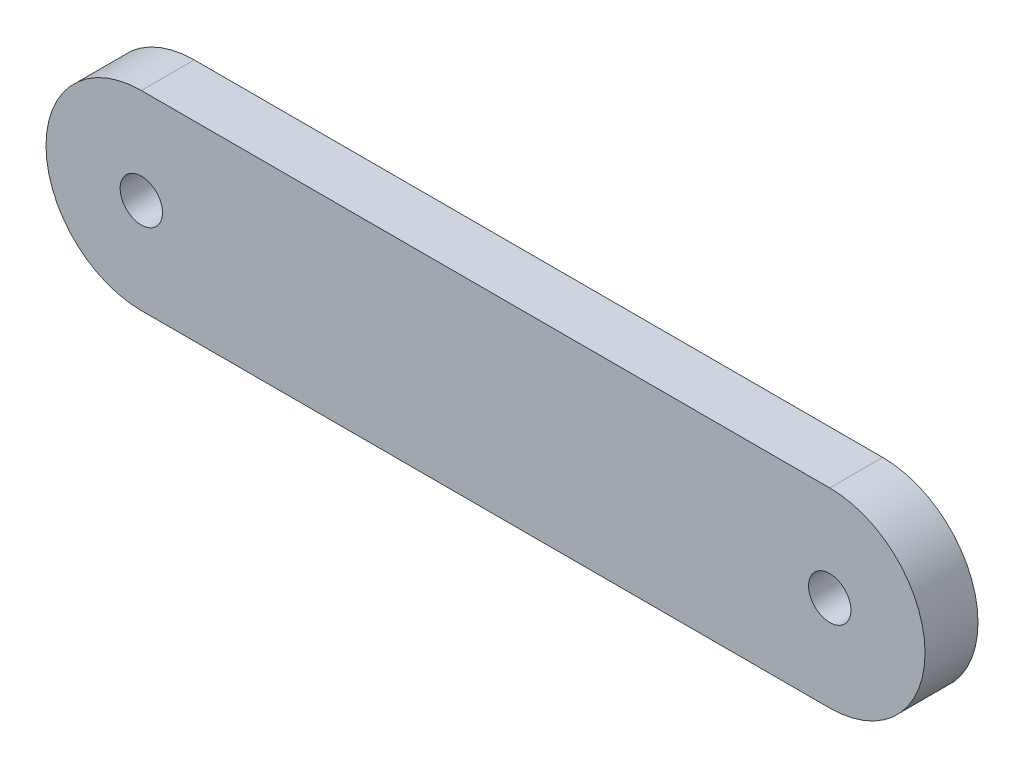
SolidWorks part; units mm, degrees
ref_plane "Plan de face" through (0, 0, 0) normal (0, 0, 1) x (1, 0, 0)
ref_plane "Plan de dessus" through (0, 0, 0) normal (0, 1, 0) x (1, 0, 0)
ref_plane "Plan de droite" through (0, 0, 0) normal (1, 0, 0) x (0, 0, -1)
sketch "Esquisse1" plane through (0, 0, 0) normal (0, 0, 1) x (1, 0, 0)
  line L0 (0, 0) -> (65, 0) construction
  line L1 (0, 9) -> (65, 9)
  line L2 (0, -9) -> (65, -9)
  arc A0 (0, 9) -> (0, -9) centre (0, 0) ccw
  arc A1 (65, -9) -> (65, 9) centre (65, 0) ccw
  circle A2 centre (0, 0) radius 2
  circle A3 centre (65, 0) radius 2
  point P3 (32.5, 0)
  dimension "D1" = 4
  dimension "D2" = 9
  dimension "D3" = 65
extrude "Boss.-Extru.1" add sketch "Esquisse1" along normal blind 5
